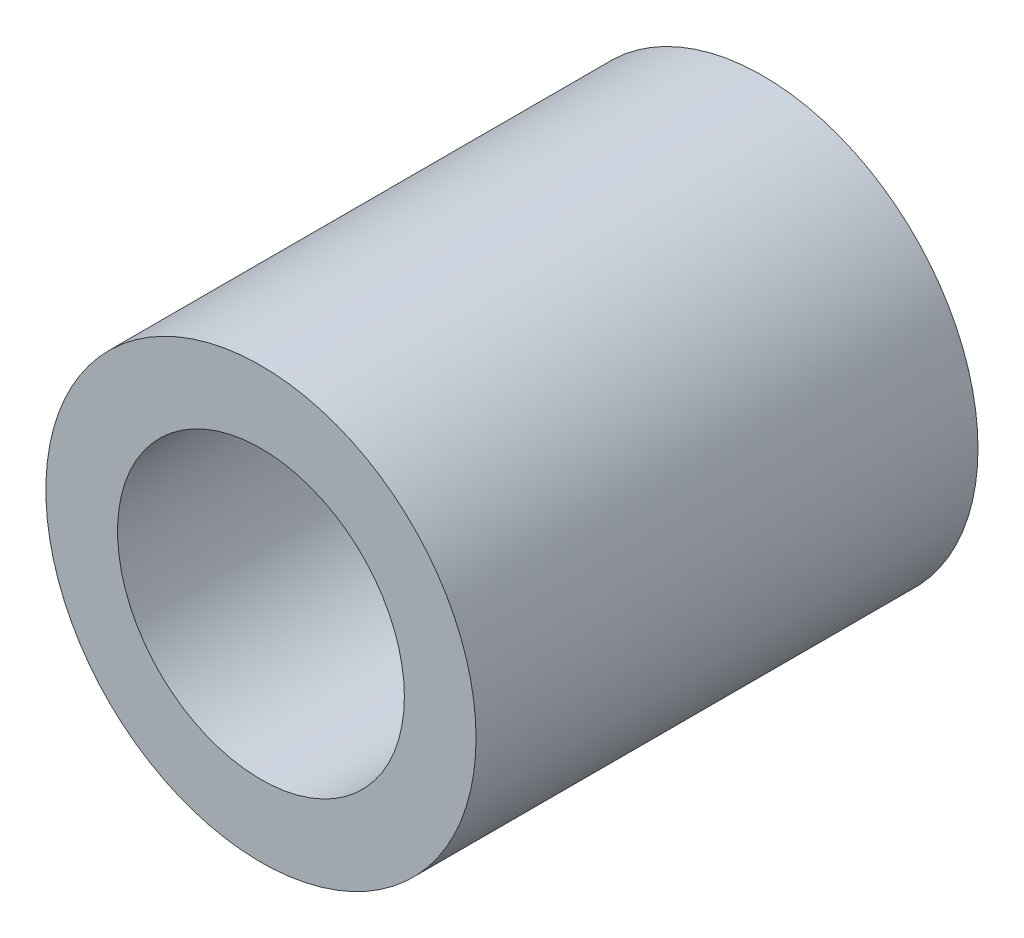
SolidWorks part; units mm, degrees
material "Alloy Steel (SS)"
ref_plane "Front Plane" through (0, 0, 0) normal (0, 0, 1) x (1, 0, 0)
ref_plane "Top Plane" through (0, 0, 0) normal (0, 1, 0) x (1, 0, 0)
ref_plane "Right Plane" through (0, 0, 0) normal (1, 0, 0) x (0, 0, -1)
sketch "Sketch1" plane through (0, 0, 0) normal (0, 0, 1) x (1, 0, 0)
  circle A0 centre (0, 0) radius 6
  circle A1 centre (0, 0) radius 4
  dimension "D1" = 12
  dimension "D2" = 8
extrude "Boss-Extrude1" add sketch "Sketch1" along normal mid plane 14
